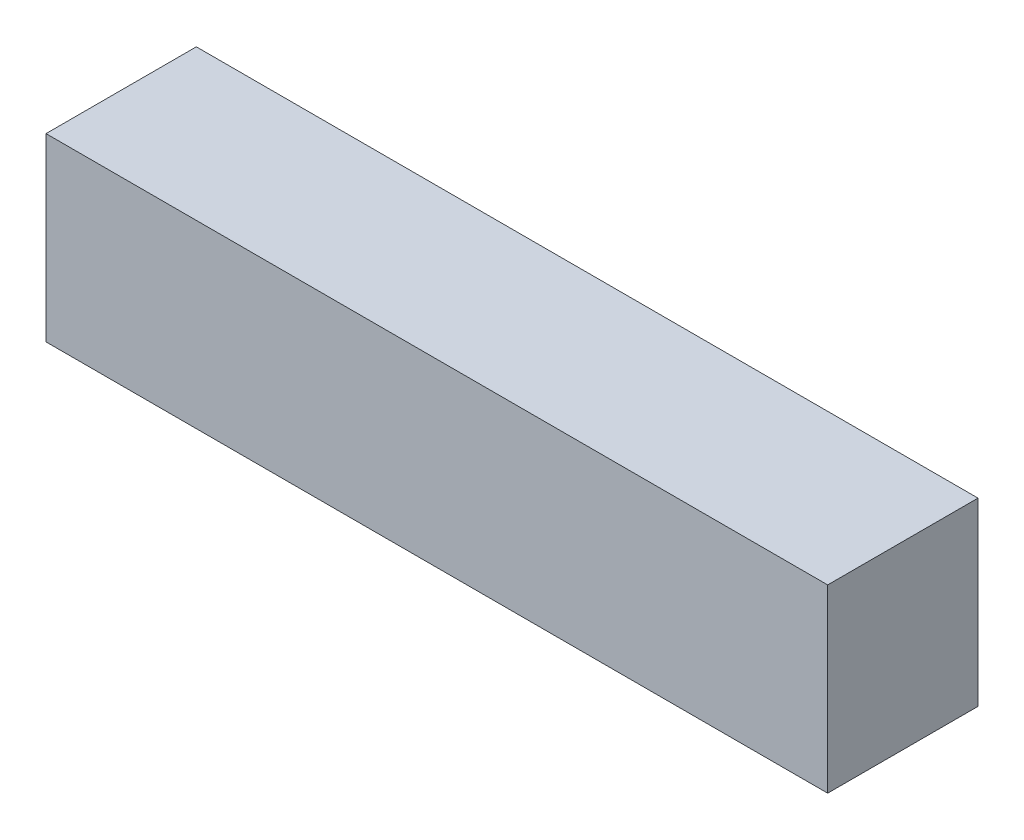
SolidWorks part; units mm, degrees
ref_plane "前视基准面" through (0, 0, 0) normal (0, 0, 1) x (1, 0, 0)
ref_plane "上视基准面" through (0, 0, 0) normal (0, 1, 0) x (1, 0, 0)
ref_plane "右视基准面" through (0, 0, 0) normal (1, 0, 0) x (0, 0, -1)
sketch "草图1" plane through (0, 0, 0) normal (0, 1, 0) x (1, 0, 0)
  line L1 (-78, -15) -> (78, -15)
  line L2 (-78, -15) -> (-78, 15)
  line L3 (-78, 15) -> (78, 15)
  line L4 (78, -15) -> (78, 15)
  line L5 (-78, -15) -> (78, 15) construction
  line L6 (-78, 15) -> (78, -15) construction
  point P0 (0, 0)
  dimension "D1" = 30
  dimension "D2" = 156
extrude "凸台-拉伸1" add sketch "草图1" along normal blind 36
